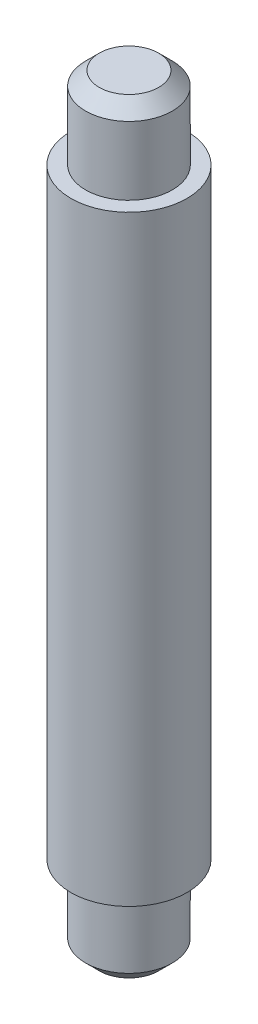
SolidWorks part; units mm, degrees
ref_plane "Plano frontal" through (0, 0, 0) normal (0, 0, 1) x (1, 0, 0)
ref_plane "Plano superior" through (0, 0, 0) normal (0, 1, 0) x (1, 0, 0)
ref_plane "Plano direito" through (0, 0, 0) normal (1, 0, 0) x (0, 0, -1)
sketch "Esboço1" plane through (0, 0, 0) normal (0, 1, 0) x (1, 0, 0)
  circle A0 centre (0, 0) radius 4.25
  circle A1 centre (0, 0) radius 3.175
  dimension "D1" = 8.5
  dimension "D2" = 6.35
extrude "Ressalto-extrusão1" add sketch "Esboço1" along normal blind 44 contours A0
sketch "Esboço2" plane through (0, 0, 0) normal (0, -1, 0) x (-1, 0, 0)
  circle A0 centre (0, 0) radius 3.175
  dimension "D1" = 6.35
extrude "Ressalto-extrusão2" add sketch "Esboço2" against normal blind 50 and the other way blind 6
chamfer "Chanfro1" distance 1 angle 45 1 edges at (0, -6, -3.175)
chamfer "Chanfro2" distance 1 angle 45 1 edges at (0, 50, -3.175)
